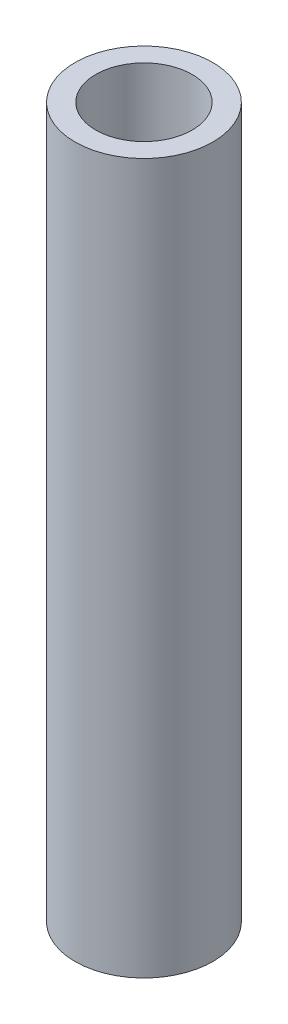
SolidWorks part; units mm, degrees
ref_plane "Front Plane" through (0, 0, 0) normal (0, 0, 1) x (1, 0, 0)
ref_plane "Top Plane" through (0, 0, 0) normal (0, 1, 0) x (1, 0, 0)
ref_plane "Right Plane" through (0, 0, 0) normal (1, 0, 0) x (0, 0, -1)
sketch "Sketch1" plane through (0, 0, 0) normal (0, 1, 0) x (1, 0, 0)
  circle A0 centre (0, 0) radius 10
  dimension "D1" = 20
extrude "Boss-Extrude1" add sketch "Sketch1" along normal blind 3
sketch "Sketch2" plane through (0, 3, 0) normal (0, 1, 0) x (1, 0, 0)
  circle A0 centre (0, 0) radius 7
  circle A1 centre (0, 0) radius 10 construction
  circle A2 centre (0, 0) radius 10
  dimension "D1" = 3
extrude "Boss-Extrude2" add sketch "Sketch2" along normal blind 100
